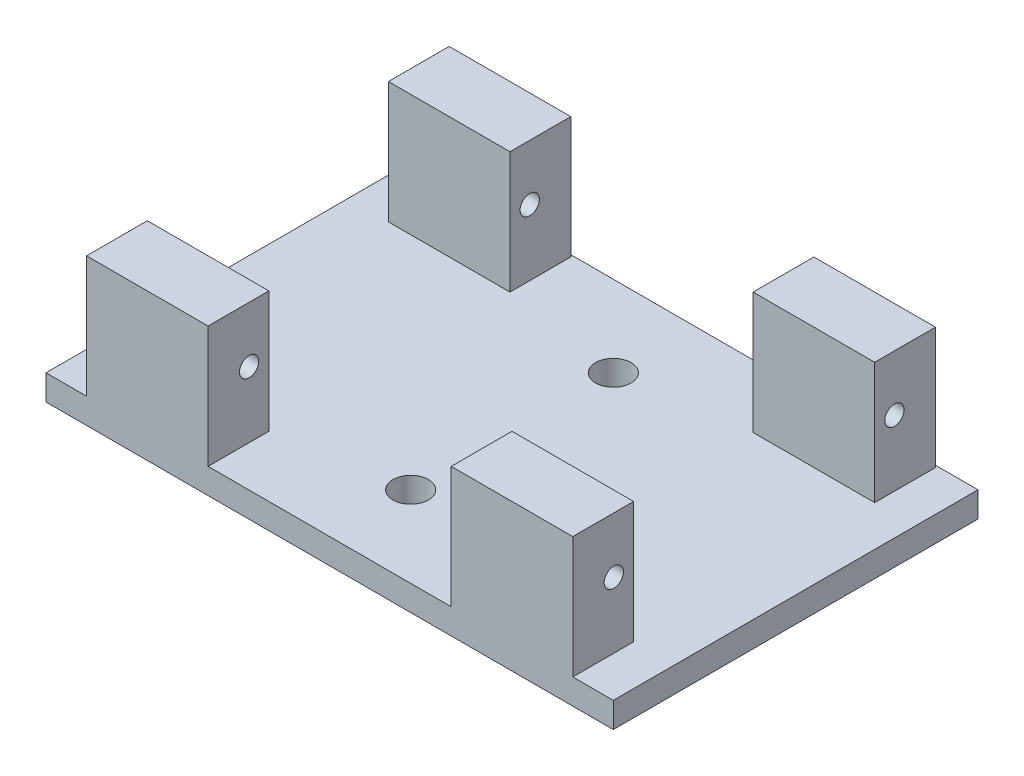
SolidWorks part; units mm, degrees
ref_plane "前视基准面" through (0, 0, 0) normal (0, 0, 1) x (1, 0, 0)
ref_plane "上视基准面" through (0, 0, 0) normal (0, 1, 0) x (1, 0, 0)
ref_plane "右视基准面" through (0, 0, 0) normal (1, 0, 0) x (0, 0, -1)
other "Configuration Table"
sketch "草图1" plane through (0, 0, 0) normal (0, 1, 0) x (1, 0, 0)
  line L1 (-28, 18) -> (28, 18)
  line L2 (-28, 18) -> (-28, -18)
  line L3 (-28, -18) -> (28, -18)
  line L4 (28, 18) -> (28, -18)
  line L5 (-28, 18) -> (28, -18) construction
  line L6 (-28, -18) -> (28, 18) construction
  point P0 (0, 0)
  dimension "D1" = 56
  dimension "D2" = 36
extrude "凸台-拉伸1" add sketch "草图1" along normal blind 2.5
sketch "草图2" plane through (0, 2.5, 0) normal (0, 1, 0) x (1, 0, 0)
  line L0 (-28, -18) -> (28, -18) construction
  line L1 (12, 17.8) -> (24, 17.8)
  line L2 (12, 17.8) -> (12, 11.8)
  line L3 (12, 11.8) -> (24, 11.8)
  line L4 (24, 17.8) -> (24, 11.8)
  line L5 (12, -12) -> (24, -12)
  line L6 (12, -12) -> (12, -18)
  line L7 (12, -18) -> (24, -18)
  line L8 (24, -12) -> (24, -18)
  line L9 (28, -18) -> (28, 18) construction
  dimension "D1" = 23.8
  dimension "D2" = 6
  dimension "D3" = 6
  dimension "D4" = 12
  dimension "D5" = 4
extrude "凸台-拉伸2" add sketch "草图2" along normal blind 12
sketch "草图3" plane through (24, 0, 0) normal (1, 0, 0) x (0, 0, -1)
  line L0 (-18, 2.5) -> (18, 2.5) construction
  line L1 (11.8, 2.5) -> (17.8, 2.5) construction
  line L2 (-12, 14.5) -> (-12, 2.5) construction
  line L3 (11.8, 14.5) -> (11.8, 2.5) construction
  circle A0 centre (-13.95, 9) radius 0.95
  circle A1 centre (13.75, 9) radius 0.95
  dimension "D1" = 6.5
  dimension "D2" = 6.5
  dimension "D3" = 1.95
  dimension "D4" = 1.95
  dimension "D5" = 1.9
  dimension "D6" = 1.9
extrude "切除-拉伸1" cut sketch "草图3" against normal through all
mirror "镜向1" about plane through (0, 0, 0) normal (1, 0, 0) of "切除-拉伸1", "凸台-拉伸2"
sketch "草图4" plane through (0, 2.5, 0) normal (0, 1, 0) x (1, 0, 0)
  circle A0 centre (0, -10) radius 1.75
  circle A1 centre (0, 10) radius 1.75
  dimension "D1" = 20
  dimension "D2" = 3.5
  dimension "D3" = 3.5
  dimension "D4" = 10
extrude "切除-拉伸2" cut sketch "草图4" against normal through all
